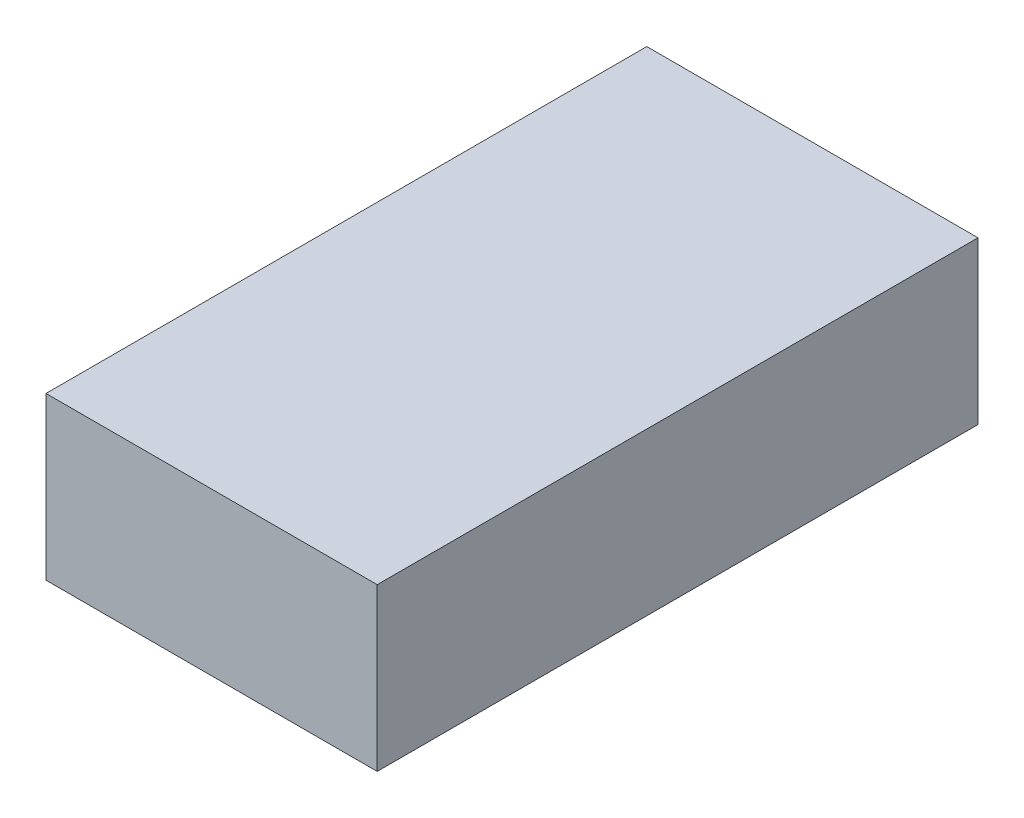
SolidWorks part; units mm, degrees
ref_plane "Front Plane" through (0, 0, 0) normal (0, 0, 1) x (1, 0, 0)
ref_plane "Top Plane" through (0, 0, 0) normal (0, 1, 0) x (1, 0, 0)
ref_plane "Right Plane" through (0, 0, 0) normal (1, 0, 0) x (0, 0, -1)
sketch "Sketch1" plane through (0, 0, 0) normal (0, 1, 0) x (1, 0, 0)
  line L1 (-21.5, 39) -> (21.5, 39)
  line L2 (-21.5, 39) -> (-21.5, -39)
  line L3 (-21.5, -39) -> (21.5, -39)
  line L4 (21.5, 39) -> (21.5, -39)
  line L5 (-21.5, 39) -> (21.5, -39) construction
  line L6 (-21.5, -39) -> (21.5, 39) construction
  point P0 (0, 0)
  dimension "D1" = 78
  dimension "D2" = 43
extrude "Boss-Extrude1" add sketch "Sketch1" along normal blind 21
